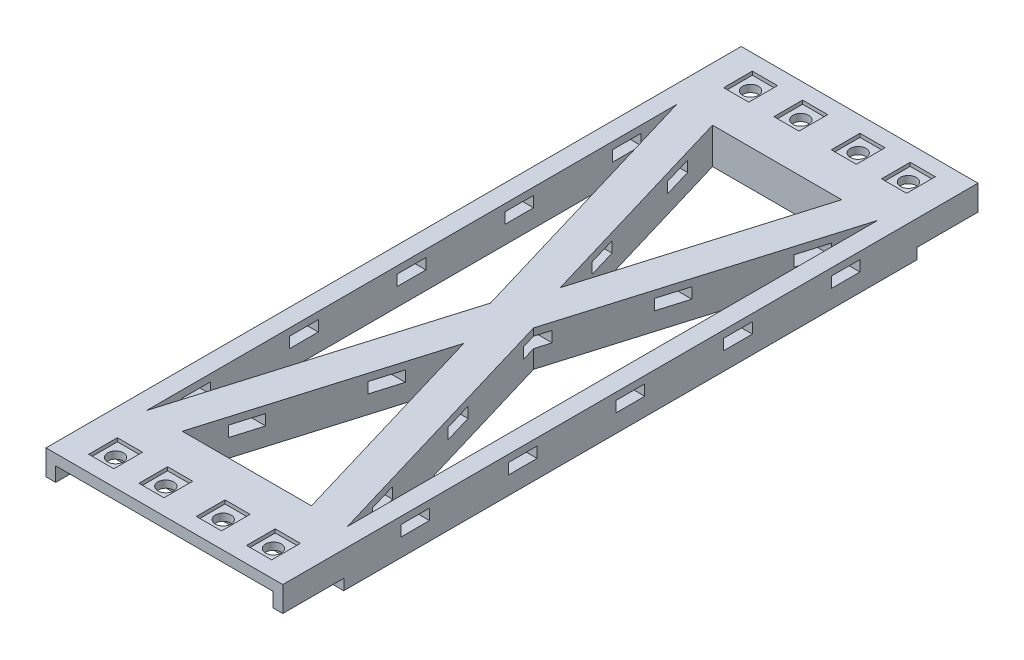
SolidWorks part; units mm, degrees
ref_plane "Front Plane" through (0, 0, 0) normal (0, 0, 1) x (1, 0, 0)
ref_plane "Top Plane" through (0, 0, 0) normal (0, 1, 0) x (1, 0, 0)
ref_plane "Right Plane" through (0, 0, 0) normal (1, 0, 0) x (0, 0, -1)
sketch "Sketch1" plane through (0, 0, 0) normal (0, 1, 0) x (1, 0, 0)
  line L1 (247.6151, -107.3627) -> (181.6151, -107.3627)
  line L2 (247.6151, -107.3627) -> (247.6151, 86.4373)
  line L3 (247.6151, 86.4373) -> (181.6151, 86.4373)
  line L4 (181.6151, -107.3627) -> (181.6151, 86.4373)
  dimension "D1" = 66
  dimension "D2" = 193.8
extrude "Boss-Extrude1" add sketch "Sketch1" along normal blind 10
sketch "Sketch2" plane through (0, 0, 0) normal (0, -1, 0) x (1, 0, 0)
  line L0 (247.6151, 107.3627) -> (247.6151, -86.4373) construction
  line L1 (181.6151, -86.4373) -> (247.6151, -86.4373)
  line L2 (181.6151, -86.4373) -> (181.6151, -69.4373)
  line L3 (181.6151, -69.4373) -> (247.6151, -69.4373)
  line L4 (247.6151, -86.4373) -> (247.6151, -69.4373)
  dimension "D1" = 17
extrude "Cut-Extrude1" cut sketch "Sketch2" against normal blind 3
sketch "Sketch3" plane through (0, 0, 0) normal (0, -1, 0) x (1, 0, 0)
  line L0 (247.6151, 107.3627) -> (247.6151, -69.4373) construction
  line L1 (181.6151, 107.3627) -> (247.6151, 107.3627)
  line L2 (181.6151, 107.3627) -> (181.6151, 90.3627)
  line L3 (181.6151, 90.3627) -> (247.6151, 90.3627)
  line L4 (247.6151, 107.3627) -> (247.6151, 90.3627)
  dimension "D1" = 17
extrude "Cut-Extrude2" cut sketch "Sketch3" against normal blind 3
sketch "Sketch4" plane through (0, 0, -86.4373) normal (0, 0, -1) x (-1, 0, 0)
  line L0 (-181.6151, 3) -> (-247.6151, 3) construction
  line L1 (-244.9151, 3) -> (-184.3151, 3)
  line L2 (-244.9151, 3) -> (-244.9151, 7)
  line L3 (-244.9151, 7) -> (-184.3151, 7)
  line L4 (-184.3151, 3) -> (-184.3151, 7)
  line L5 (-247.6151, 10) -> (-247.6151, 3) construction
  line L6 (-181.6151, 10) -> (-181.6151, 3) construction
  dimension "D1" = 2.7
  dimension "D2" = 2.7
  dimension "D3" = 4
extrude "Cut-Extrude3" cut sketch "Sketch4" against normal up to surface (17 mm away) up to face at (214.6151, 1.5, -69.4373)
sketch "Sketch5" plane through (0, 0, 107.3627) normal (0, 0, 1) x (1, 0, 0)
  line L0 (247.6151, 3) -> (181.6151, 3) construction
  line L1 (184.3151, 3) -> (244.9151, 3)
  line L2 (184.3151, 3) -> (184.3151, 7)
  line L3 (184.3151, 7) -> (244.9151, 7)
  line L4 (244.9151, 3) -> (244.9151, 7)
  line L5 (247.6151, 10) -> (247.6151, 3) construction
  line L6 (181.6151, 10) -> (181.6151, 3) construction
  dimension "D1" = 2.7
  dimension "D2" = 4
  dimension "D3" = 2.7
extrude "Cut-Extrude4" cut sketch "Sketch5" against normal up to surface (17 mm away) up to face at (214.6151, 1.5, 90.3627)
sketch "Sketch6" plane through (0, 0, 0) normal (0, -1, 0) x (1, 0, 0)
  circle A0 centre (236.6151, 98.9627) radius 2.2
  circle A1 centre (222.6151, 98.9627) radius 2.2
  circle A2 centre (206.6151, 98.9627) radius 2.2
  circle A3 centre (192.6151, 98.9627) radius 2.2
  circle A4 centre (236.6151, -78.0373) radius 2.2
  circle A5 centre (222.6151, -78.0373) radius 2.2
  circle A6 centre (206.6151, -78.0373) radius 2.2
  circle A7 centre (192.6151, -78.0373) radius 2.2
  dimension "D1" = 4.4
  dimension "D2" = 4.4
  dimension "D3" = 4.4
  dimension "D4" = 4.4
  dimension "D5" = 4.4
  dimension "D6" = 4.4
  dimension "D7" = 4.4
  dimension "D8" = 4.4
extrude "Cut-Extrude5" cut sketch "Sketch6" against normal up to surface (10 mm away) up to face at (214.6151, 10, 10.4627)
sketch "Sketch7" plane through (0, 10, 0) normal (0, 1, 0) x (1, 0, 0)
  line L1 (189.1151, 82.0373) -> (196.1151, 82.0373)
  line L2 (189.1151, 82.0373) -> (189.1151, 74.0373)
  line L3 (189.1151, 74.0373) -> (196.1151, 74.0373)
  line L4 (196.1151, 82.0373) -> (196.1151, 74.0373)
  line L5 (203.1151, 82.0373) -> (210.1151, 82.0373)
  line L6 (203.1151, 82.0373) -> (203.1151, 74.0373)
  line L7 (203.1151, 74.0373) -> (210.1151, 74.0373)
  line L8 (210.1151, 82.0373) -> (210.1151, 74.0373)
  line L9 (219.1151, 82.0373) -> (226.1151, 82.0373)
  line L10 (219.1151, 82.0373) -> (219.1151, 74.0373)
  line L11 (219.1151, 74.0373) -> (226.1151, 74.0373)
  line L12 (226.1151, 82.0373) -> (226.1151, 74.0373)
  line L13 (233.1151, 82.0373) -> (240.1151, 82.0373)
  line L14 (233.1151, 82.0373) -> (233.1151, 74.0373)
  line L15 (233.1151, 74.0373) -> (240.1151, 74.0373)
  line L16 (240.1151, 82.0373) -> (240.1151, 74.0373)
  line L17 (233.1151, -94.9627) -> (240.1151, -94.9627)
  line L18 (233.1151, -94.9627) -> (233.1151, -102.9627)
  line L19 (233.1151, -102.9627) -> (240.1151, -102.9627)
  line L20 (240.1151, -94.9627) -> (240.1151, -102.9627)
  line L21 (219.1151, -94.9627) -> (226.1151, -94.9627)
  line L22 (219.1151, -94.9627) -> (219.1151, -102.9627)
  line L23 (219.1151, -102.9627) -> (226.1151, -102.9627)
  line L24 (226.1151, -94.9627) -> (226.1151, -102.9627)
  line L25 (203.1151, -94.9627) -> (210.1151, -94.9627)
  line L26 (203.1151, -94.9627) -> (203.1151, -102.9627)
  line L27 (203.1151, -102.9627) -> (210.1151, -102.9627)
  line L28 (210.1151, -94.9627) -> (210.1151, -102.9627)
  line L29 (189.1151, -94.9627) -> (196.1151, -94.9627)
  line L30 (189.1151, -94.9627) -> (189.1151, -102.9627)
  line L31 (189.1151, -102.9627) -> (196.1151, -102.9627)
  line L32 (196.1151, -94.9627) -> (196.1151, -102.9627)
  circle A0 centre (192.6151, -98.9627) radius 2.2 construction
  circle A1 centre (206.6151, -98.9627) radius 2.2 construction
  circle A2 centre (222.6151, -98.9627) radius 2.2 construction
  circle A3 centre (236.6151, -98.9627) radius 2.2 construction
  circle A4 centre (192.6151, 78.0373) radius 2.2 construction
  circle A5 centre (206.6151, 78.0373) radius 2.2 construction
  circle A6 centre (222.6151, 78.0373) radius 2.2 construction
  circle A7 centre (236.6151, 78.0373) radius 2.2 construction
  dimension "D2" = 3.5
  dimension "D3" = 4
  dimension "D4" = 4
  dimension "D6" = 3.5
  dimension "D7" = 4
  dimension "D8" = 4
  dimension "D10" = 3.5
  dimension "D11" = 4
  dimension "D12" = 4
  dimension "D22" = 3.5
  dimension "D1" = 3.5
  dimension "D5" = 3.5
  dimension "D9" = 3.5
  dimension "D13" = 3.5
  dimension "D14" = 3.5
  dimension "D15" = 4
  dimension "D16" = 4
  dimension "D17" = 4
  dimension "D18" = 4
  dimension "D19" = 3.5
  dimension "D20" = 3.5
  dimension "D21" = 3.5
  dimension "D23" = 4
  dimension "D24" = 4
  dimension "D25" = 4
  dimension "D26" = 4
  dimension "D27" = 3.5
  dimension "D28" = 3.5
  dimension "D29" = 3.5
  dimension "D30" = 3.5
  dimension "D31" = 4
  dimension "D32" = 4
extrude "Cut-Extrude6" cut sketch "Sketch7" against normal blind 1
sketch "Sketch8" plane through (0, 10, 0) normal (0, 1, 0) x (1, 0, 0)
  line L0 (186.6151, 63.4373) -> (186.6151, -84.3627)
  line L1 (186.6151, -84.3627) -> (208.6151, -10.4627)
  line L2 (208.6151, -10.4627) -> (186.6151, 63.4373)
  line L3 (196.6151, 63.4373) -> (214.6151, 2.9737)
  line L4 (214.6151, 2.9737) -> (232.6151, 63.4373)
  line L5 (232.6151, 63.4373) -> (196.6151, 63.4373)
  line L6 (214.6151, -23.899) -> (196.6151, -84.3627)
  line L7 (196.6151, -84.3627) -> (232.6151, -84.3627)
  line L8 (232.6151, -84.3627) -> (214.6151, -23.899)
  line L9 (242.6151, 63.4373) -> (242.6151, -84.3627)
  line L10 (242.6151, -84.3627) -> (220.6151, -10.4627)
  line L11 (220.6151, -10.4627) -> (242.6151, 63.4373)
  line L12 (181.6151, 86.4373) -> (181.6151, -107.3627) construction
  line L13 (247.6151, 86.4373) -> (181.6151, 86.4373) construction
  line L14 (247.6151, -107.3627) -> (247.6151, 86.4373) construction
  line L15 (181.6151, -107.3627) -> (247.6151, -107.3627) construction
  point P20 (186.6151, -10.4627)
  point P21 (242.6151, -10.4627)
  dimension "D1" = 36
  dimension "D2" = 15
  dimension "D3" = 23
  dimension "D4" = 36
  dimension "D5" = 15
  dimension "D6" = 23
  dimension "D7" = 23
  dimension "D8" = 23
  dimension "D9" = 23
  dimension "D10" = 23
  dimension "D11" = 22
  dimension "D12" = 22
  dimension "D13" = 5
  dimension "D14" = 5
  dimension "D15" = 0
  dimension "D16" = 0
extrude "Cut-Extrude7" cut sketch "Sketch8" against normal through all
sketch "Sketch9" plane through (247.6151, 0, 0) normal (1, 0, 0) x (0, 0, -1)
  line L0 (-107.3627, 10) -> (86.4373, 10) construction
  line L1 (-74.4627, 8) -> (-66.4627, 8)
  line L2 (-74.4627, 8) -> (-74.4627, 5)
  line L3 (-74.4627, 5) -> (-66.4627, 5)
  line L4 (-66.4627, 8) -> (-66.4627, 5)
  line L5 (-44.4627, 8) -> (-44.4627, 5)
  line L6 (-44.4627, 8) -> (-36.4627, 8)
  line L7 (-36.4627, 8) -> (-36.4627, 5)
  line L8 (-44.4627, 5) -> (-36.4627, 5)
  line L9 (-14.4627, 8) -> (-14.4627, 5)
  line L10 (-14.4627, 8) -> (-6.4627, 8)
  line L11 (-6.4627, 8) -> (-6.4627, 5)
  line L12 (-14.4627, 5) -> (-6.4627, 5)
  line L13 (15.5373, 8) -> (15.5373, 5)
  line L14 (15.5373, 8) -> (23.5373, 8)
  line L15 (23.5373, 8) -> (23.5373, 5)
  line L16 (15.5373, 5) -> (23.5373, 5)
  line L17 (45.5373, 8) -> (45.5373, 5)
  line L18 (45.5373, 8) -> (53.5373, 8)
  line L19 (53.5373, 8) -> (53.5373, 5)
  line L20 (45.5373, 5) -> (53.5373, 5)
  line L21 (-90.3627, 3) -> (-90.3627, 0) construction
  dimension "D1" = 8
  dimension "D2" = 3
  dimension "D3" = 2
  dimension "D5" = 15.9
  dimension "D4" = 5
extrude "Cut-Extrude8" cut sketch "Sketch9" against normal through all
